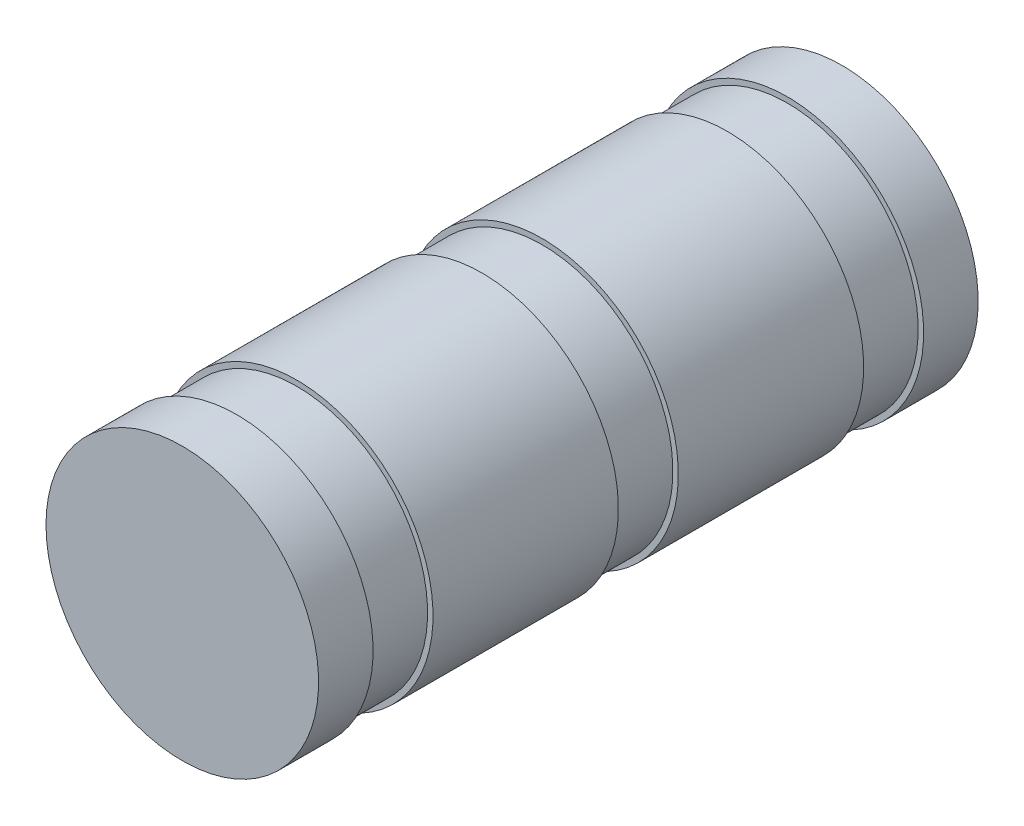
SolidWorks part; units mm, degrees
material "Plain Carbon Steel"
ref_plane "Front Plane" through (0, 0, 0) normal (0, 0, 1) x (1, 0, 0)
ref_plane "Top Plane" through (0, 0, 0) normal (0, 1, 0) x (1, 0, 0)
ref_plane "Right Plane" through (0, 0, 0) normal (1, 0, 0) x (0, 0, -1)
sketch "Sketch1" plane through (0, 0, 0) normal (0, 1, 0) x (1, 0, 0)
  line L0 (0, 0) -> (-2.5, 0)
  line L1 (-2.5, 0) -> (-2.5, 1)
  line L2 (-2.5, 1) -> (-2.4, 1)
  line L3 (-2.4, 1) -> (-2.4, 2.1)
  line L4 (-2.4, 2.1) -> (-2.5, 2.1)
  line L5 (-2.5, 2.1) -> (-2.5, 5.5)
  line L6 (-2.5, 5.5) -> (-2.4, 5.5)
  line L7 (-2.4, 5.5) -> (-2.4, 6.6)
  line L8 (-2.4, 6.6) -> (-2.5, 6.6)
  line L9 (-2.5, 6.6) -> (-2.5, 10)
  line L10 (-2.5, 10) -> (-2.4, 10)
  line L11 (-2.4, 10) -> (-2.4, 11.1)
  line L12 (-2.4, 11.1) -> (-2.5, 11.1)
  line L13 (-2.5, 11.1) -> (-2.5, 12.1)
  line L14 (-2.5, 12.1) -> (0, 12.1)
  line L15 (0, 12.1) -> (0, 0)
  dimension "D1" = 2.5
  dimension "D2" = 1
  dimension "D3" = 1.1
  dimension "D4" = 12.1
  dimension "D5" = 3.4
  dimension "D6" = 2.4
revolve "Revolve1" add sketch "Sketch1" angle 360 about L15
equation "\"weightkg\"= \"SW-Mass\" / 1000"
